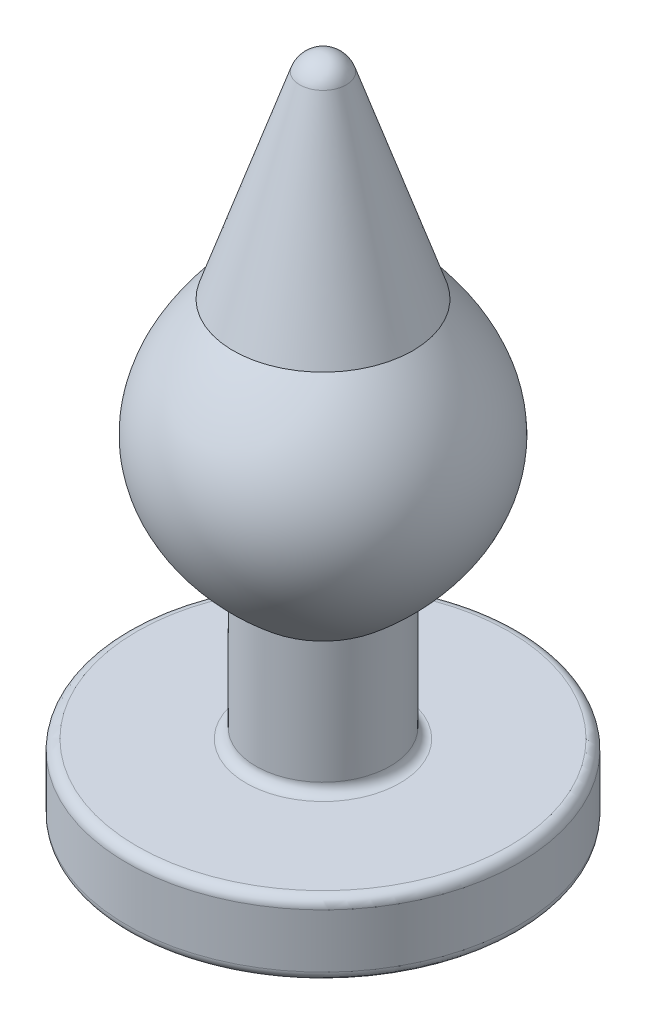
SolidWorks part; units mm, degrees
ref_plane "Front Plane" through (0, 0, 0) normal (0, 0, 1) x (1, 0, 0)
ref_plane "Top Plane" through (0, 0, 0) normal (0, 1, 0) x (1, 0, 0)
ref_plane "Right Plane" through (0, 0, 0) normal (1, 0, 0) x (0, 0, -1)
sketch "Sketch1" plane through (0, 0, 0) normal (0, 0, 1) x (1, 0, 0)
  line L1 (3.0074, 42.7517) -> (11.6522, 17.2117)
  line L2 (11.6522, 17.2117) -> (32.2079, -43.5179) construction
  line L3 (8.7045, -15.0869) -> (8.7045, -30.9388)
  line L4 (0, 44.9088) -> (0, -41.7338)
  line L5 (0, -41.7338) -> (24.13, -41.7338)
  line L7 (9.9745, -32.2088) -> (24.13, -32.2088)
  line L8 (25.4, -40.4638) -> (25.4, -33.4788)
  arc A0 (3.0074, 42.7517) -> (0, 44.9088) centre (0, 41.7338) ccw
  arc A1 (24.13, -41.7338) -> (25.4, -40.4638) centre (24.13, -40.4638) ccw
  arc A2 (24.13, -32.2088) -> (25.4, -33.4788) centre (24.13, -33.4788) cw
  arc A3 (8.7045, -30.9388) -> (9.9745, -32.2088) centre (9.9745, -30.9388) ccw
  spline S0 degree 2 poles (11.6522, 17.2117) (27.092, 0.0776) (8.7045, -15.0869) knots 0 0 0 1 1 1
  point P0 (8.7045, -15.0869)
  point P4 (0, 0)
  point P23 (25.4, -41.7338)
  point P26 (25.4, -32.2088)
  dimension "D2" = 6.35
  dimension "D5" = 1.27
  dimension "D1" = 1.27
  dimension "D3" = 9.525
  dimension "D4" = 25.4
revolve "Revolve3" add sketch "Sketch1" angle 360 about L4
